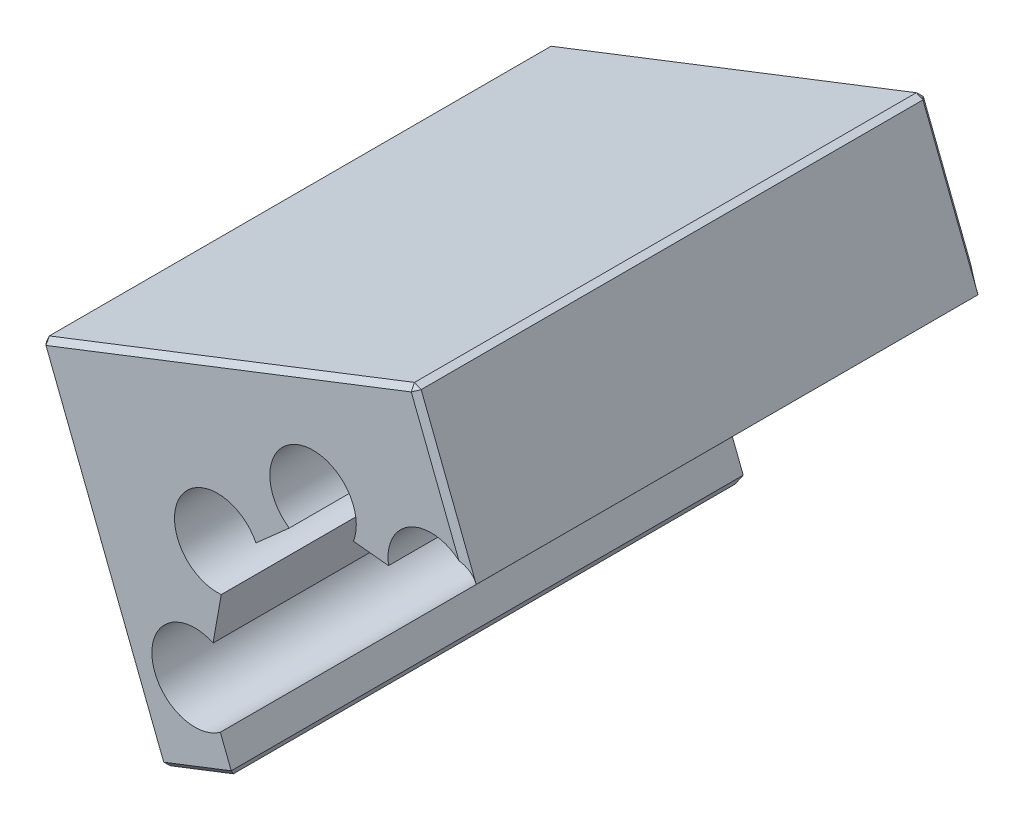
SolidWorks part; units mm, degrees
ref_plane "前基準面" through (0, 0, 0) normal (0, 0, 1) x (1, 0, 0)
ref_plane "上基準面" through (0, 0, 0) normal (0, 1, 0) x (1, 0, 0)
ref_plane "右基準面" through (0, 0, 0) normal (1, 0, 0) x (0, 0, -1)
sketch "草圖1" plane through (0, 0, 12827.7351) normal (0, 0, 1) x (1, 0, 0)
  line L0 (-121.0055, -94.6668) -> (-109.956, -32.2463) construction
  line L1 (-109.956, -32.2463) -> (-63.2989, 9.2018) construction
  line L2 (-63.2989, 9.2018) -> (-5.7089, 3.2255) construction
  line L3 (-121.0055, -94.6668) -> (-112.1178, -75.6402) construction
  line L4 (-112.1178, -75.6402) -> (-108.1397, -53.1676)
  line L5 (-108.1397, -53.1676) -> (-109.956, -32.2463) construction
  line L6 (-109.956, -32.2463) -> (-91.1815, -22.8379) construction
  line L7 (-91.1815, -22.8379) -> (-74.9152, -8.4262)
  line L8 (-74.9152, -8.4262) -> (-63.2989, 9.2018) construction
  line L9 (-63.2989, 9.2018) -> (-43.5799, 1.6622) construction
  line L10 (-43.5799, 1.6622) -> (-26.446, -0.0869)
  line L11 (-26.446, -0.0869) -> (-5.7089, 3.2255) construction
  line L12 (-108.5754, -111.5928) -> (-102.3514, -127.5624)
  line L14 (13.8576, 10.8513) -> (-13.9295, 82.1483)
  line L15 (-102.3514, -127.5624) -> (-137.6384, -141.3151)
  line L16 (-137.6384, -141.3151) -> (-196.9331, 10.825)
  line L17 (-196.9331, 10.825) -> (-13.9295, 82.1483)
  arc A1 (-112.1178, -75.6402) -> (-108.5754, -111.5928) centre (-121.0055, -94.6668) ccw
  arc A2 (-91.1815, -22.8379) -> (-108.1397, -53.1676) centre (-109.956, -32.2463) ccw
  arc A3 (-43.5799, 1.6622) -> (-74.9152, -8.4262) centre (-63.2989, 9.2018) ccw
  arc A4 (13.8576, 10.8513) -> (-26.446, -0.0869) centre (-5.7089, 3.2255) ccw
  dimension "D1" = 15
  dimension "D2" = 15
  dimension "D3" = 15
  dimension "D4" = 15
  dimension "D5" = 15
  dimension "D6" = 15
extrude "填料-伸長2" add sketch "草圖1" against normal blind 250
chamfer "導角1" distance 2.5 angle 45 12 edges at (-105.4313, 46.4867, 12577.7351) (-0.036, 46.4998, 12577.7351) (-13.9295, 82.1483, 12702.7351) (-167.2857, -65.245, 12577.7351) (-196.9331, 10.825, 12702.7351) (-102.3514, -127.5624, 12702.7351) (-119.9949, -134.4387, 12577.7351) (-137.6384, -141.3151, 12702.7351) (-119.9949, -134.4387, 12827.7351) (-167.2857, -65.245, 12827.7351) (-105.4313, 46.4867, 12827.7351) (-0.036, 46.4998, 12827.7351)
equation "\"ㄉ200\"=10"
